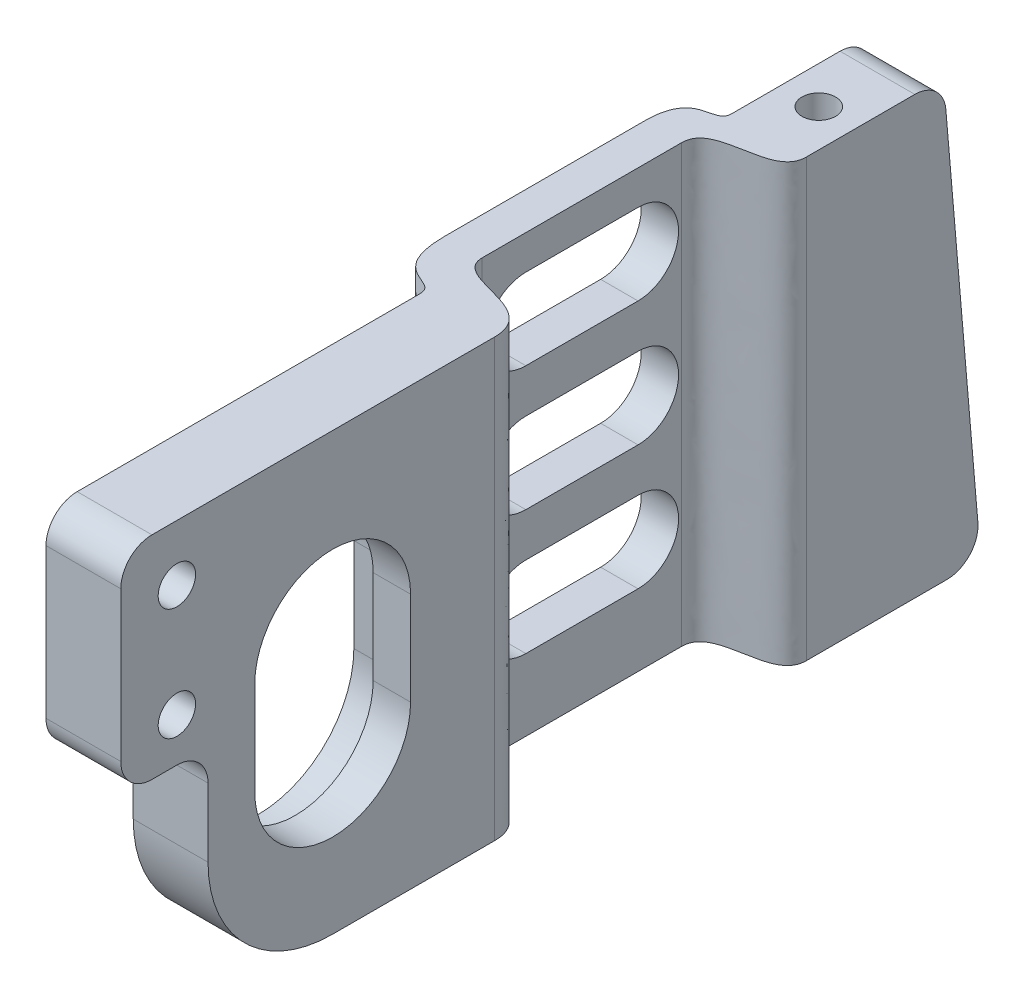
SolidWorks part; units mm, degrees
ref_plane "Front Plane" through (0, 0, 0) normal (0, 0, 1) x (1, 0, 0)
ref_plane "Top Plane" through (0, 0, 0) normal (0, 1, 0) x (1, 0, 0)
ref_plane "Right Plane" through (0, 0, 0) normal (1, 0, 0) x (0, 0, -1)
sketch "Sketch3" plane through (0, 0, 0) normal (0, 1, 0) x (1, 0, 0)
  line L0 (0, 69) -> (0, 0) construction
  line L1 (0, 69) -> (-6, 69)
  line L2 (-6, 69) -> (-6, 55)
  line L3 (0, 0) -> (-6, 0)
  line L4 (-6, 0) -> (-6, 30)
  line L5 (-6, 51) -> (-6, 35)
  line L6 (-9, 51) -> (-9, 35)
  line L7 (0, 0) -> (0, 30)
  line L8 (0, 69) -> (0, 55)
  line L9 (0, 17.85) -> (0, 23.6189) construction
  line L10 (-6, 13.503) -> (-6, 19.9186) construction
  line L11 (-6, 22.5448) -> (-6, 18.8386) construction
  line L12 (-9, 18.4101) -> (-9, 14.7404) construction
  line L13 (0, -6.29) -> (0, -0.0415) construction
  line L14 (-6, -2.2539) -> (-6, 3.7004) construction
  line L15 (-6, -6.3145) -> (-6, -2.2639) construction
  line L16 (-9, -0.8189) -> (-9, 3.9951) construction
  spline S0 degree 3 poles (0, 55) (0, 52.0887) (-6, 53.8428) (-6, 51) knots 0 0 0 0 1 1 1 1
  spline S1 degree 3 poles (-9, 51) (-9, 55.3071) (-6, 53.4557) (-6, 55) knots 0 0 0 0 1 1 1 1
  spline S2 degree 3 poles (-9, 35) (-9, 30.1021) (-6, 31.6877) (-6, 30) knots 0 0 0 0 1 1 1 1
  spline S3 degree 3 poles (-6, 35) (-6, 32.3364) (0, 33.9564) (0, 30) knots 0 0 0 0 1 1 1 1
  dimension "D1" = 69
  dimension "D2" = 6
  dimension "D3" = 3
  dimension "D4" = 30
  dimension "D5" = 14
  dimension "D6" = 4
  dimension "D7" = 5
extrude "Boss-Extrude1" add sketch "Sketch3" along normal blind 35
sketch "Sketch4" plane through (-9, 0, 0) normal (-1, 0, 0) x (0, 0, 1)
  line L0 (-69, 35) -> (-66, 35)
  line L1 (-59, -5.5218) -> (-59, 11.1026) construction
  line L2 (-69, 35) -> (-55, 35) construction
  line L3 (-69, 0) -> (-69, 35)
  line L4 (-66, 35) -> (-69, 0)
  line L5 (-47.5, 29) -> (-38.5, 29) construction
  line L6 (-47.5, 32.25) -> (-38.5, 32.25)
  line L7 (-47.5, 25.75) -> (-38.5, 25.75)
  line L8 (-51, 35) -> (-51, 0) construction
  line L9 (-35, 35) -> (-35, 0) construction
  line L10 (-43, 38.0091) -> (-43, 1.1359) construction
  line L11 (-47.5, 19) -> (-38.5, 19) construction
  line L12 (-47.5, 22.25) -> (-38.5, 22.25)
  line L13 (-47.5, 15.75) -> (-38.5, 15.75)
  line L14 (-47.5, 9) -> (-38.5, 9) construction
  line L15 (-47.5, 12.25) -> (-38.5, 12.25)
  line L16 (-47.5, 5.75) -> (-38.5, 5.75)
  line L17 (-30, 35) -> (0, 35) construction
  line L18 (0, 35) -> (0, 0) construction
  line L19 (0, 18) -> (-7, 18)
  line L20 (-7, 18) -> (-7, 0)
  line L21 (0, 0) -> (-30, 0) construction
  line L22 (0, 18) -> (0, 0)
  line L23 (0, 0) -> (-7, 0)
  line L24 (-17, 20.5) -> (-17, 13) construction
  line L25 (-10.75, 20.5) -> (-10.75, 13)
  line L26 (-23.25, 20.5) -> (-23.25, 13)
  line L27 (-51, 35) -> (-35, 35) construction
  arc A0 (-47.5, 32.25) -> (-47.5, 25.75) centre (-47.5, 29) ccw
  arc A1 (-38.5, 25.75) -> (-38.5, 32.25) centre (-38.5, 29) ccw
  arc A2 (-47.5, 22.25) -> (-47.5, 15.75) centre (-47.5, 19) ccw
  arc A3 (-38.5, 15.75) -> (-38.5, 22.25) centre (-38.5, 19) ccw
  arc A4 (-47.5, 12.25) -> (-47.5, 5.75) centre (-47.5, 9) ccw
  arc A5 (-38.5, 5.75) -> (-38.5, 12.25) centre (-38.5, 9) ccw
  circle A6 centre (-4.5, 30.5) radius 1.5
  circle A7 centre (-4.5, 21.5) radius 1.5
  arc A8 (-10.75, 20.5) -> (-23.25, 20.5) centre (-17, 20.5) ccw
  arc A9 (-23.25, 13) -> (-10.75, 13) centre (-17, 13) ccw
  point P9 (-43, 29)
  point P24 (-43, 19)
  point P31 (-43, 9)
  point P53 (-17, 16.75)
  dimension "D2" = 3.5
  dimension "D6" = 3
  dimension "D7" = 3
  dimension "D14" = 7.5
  dimension "D16" = 13
  dimension "D1" = 3
  dimension "D3" = 3.5
  dimension "D5" = 10
  dimension "D8" = 4.5
  dimension "D9" = 4.5
  dimension "D10" = 9
  dimension "D11" = 17
  dimension "D12" = 7
  dimension "D13" = 12.5
  dimension "D15" = 42
  dimension "D17" = 6.5
  dimension "D18" = 6
  dimension "D19" = 10
  dimension "D4" = 3
extrude "Cut-Extrude1" cut sketch "Sketch4" against normal up to next
sketch "Sketch7" plane through (-6, 0, 0) normal (-1, 0, 0) x (0, 0, 1)
  line L0 (-17, 20.5) -> (-17, 13) construction
  line L1 (-9.3, 20.5) -> (-9.3, 13)
  line L2 (-24.7, 20.5) -> (-24.7, 13)
  circle A0 centre (-4.5, 30.5) radius 3.25
  circle A1 centre (-4.5, 21.5) radius 3.25
  circle A3 centre (-4.5, 30.5) radius 1.5 construction
  circle A4 centre (-4.5, 21.5) radius 1.5 construction
  arc A5 (-9.3, 20.5) -> (-24.7, 20.5) centre (-17, 20.5) ccw
  arc A6 (-24.7, 13) -> (-9.3, 13) centre (-17, 13) ccw
  point P12 (-17, 16.75)
  dimension "D1" = 6.5
  dimension "D2" = 6.5
  dimension "D3" = 15.4
extrude "Cut-Extrude2" cut sketch "Sketch7" against normal blind 3
sketch "Sketch10" plane through (0, 0, 0) normal (0, -1, 0) x (1, 0, 0)
  line L0 (0, -69) -> (-6, -69) construction
  circle A0 centre (-3, -59) radius 1.35
  circle A1 centre (-3, -26) radius 1.35
  point P6 (-3, -69)
  dimension "D1" = 2.7
  dimension "D2" = 2.7
  dimension "D3" = 10
  dimension "D4" = 33
extrude "Cut-Extrude3" cut sketch "Sketch10" against normal blind 10
sketch "Sketch11" plane through (0, 35, 0) normal (0, 1, 0) x (1, 0, 0)
  line L0 (0, 69) -> (-6, 69) construction
  circle A0 centre (-3, 59) radius 1.35
  point P4 (-3, 69)
  dimension "D1" = 2.7
  dimension "D2" = 10
extrude "Cut-Extrude4" cut sketch "Sketch11" against normal blind 10
fillet "Fillet1" radius 2.5 5 edges at (-3, 35, 0) (-3, 18, 0) (-3, 0, -69) (-3, 35, -66) (-3, 18, -7)
fillet "Fillet2" radius 10 1 edges at (-3, 0, -7)
